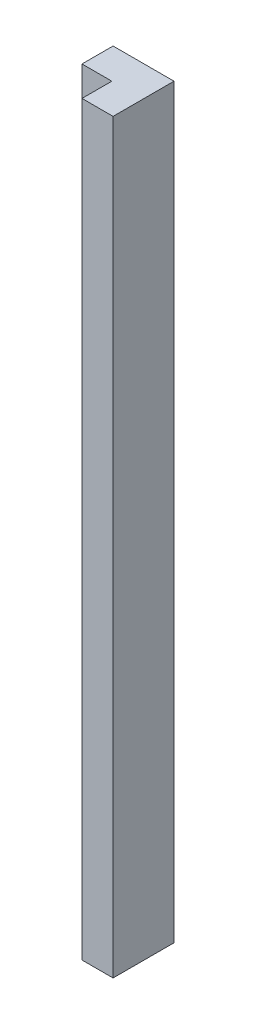
SolidWorks part; units mm, degrees
ref_plane "Front Plane" through (0, 0, 0) normal (0, 0, 1) x (1, 0, 0)
ref_plane "Top Plane" through (0, 0, 0) normal (0, 1, 0) x (1, 0, 0)
ref_plane "Right Plane" through (0, 0, 0) normal (1, 0, 0) x (0, 0, -1)
sketch "Sketch1" plane through (0, 0, 0) normal (0, 0, 1) x (1, 0, 0)
  line L1 (0, 0) -> (9.8, 0)
  line L2 (0, 0) -> (0, 120)
  line L3 (0, 120) -> (9.8, 120)
  line L4 (9.8, 0) -> (9.8, 120)
  dimension "D1" = 120
  dimension "D2" = 9.8
extrude "Boss-Extrude1" add sketch "Sketch1" along normal blind 5
sketch "Sketch2" plane through (0, 0, 5) normal (0, 0, 1) x (1, 0, 0)
  line L1 (9.8, 0) -> (4.8, 0)
  line L2 (9.8, 0) -> (9.8, 120)
  line L3 (9.8, 120) -> (4.8, 120)
  line L4 (4.8, 0) -> (4.8, 120)
  dimension "D1" = 120
  dimension "D2" = 5
extrude "Boss-Extrude2" add sketch "Sketch2" along normal blind 4.8
